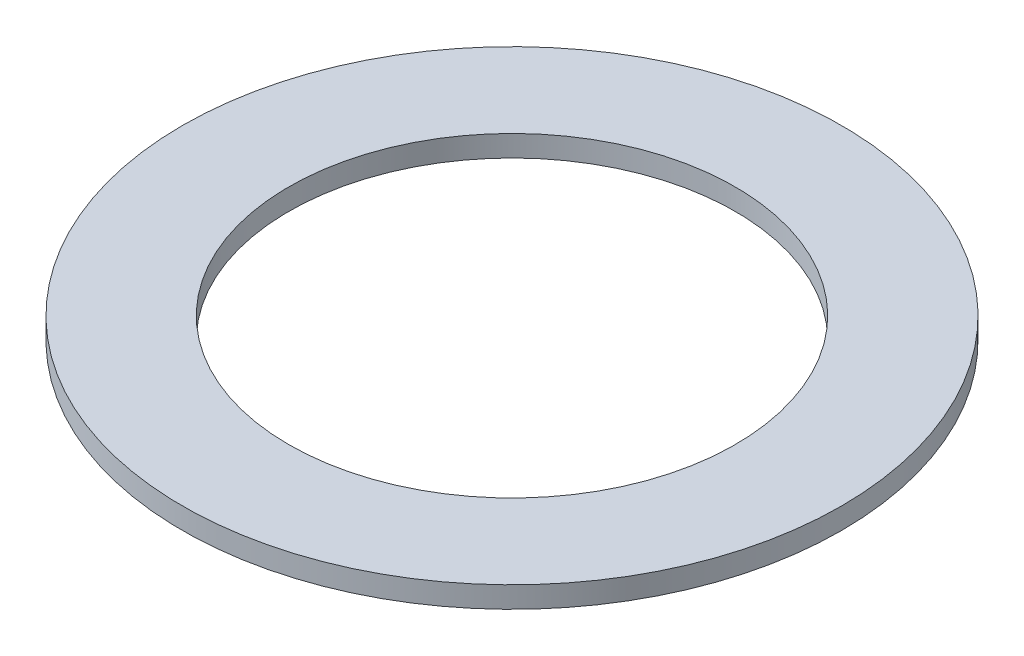
SolidWorks part; units mm, degrees
material "Plain Carbon Steel"
ref_plane "Front Plane" through (0, 0, 0) normal (0, 0, 1) x (1, 0, 0)
ref_plane "Top Plane" through (0, 0, 0) normal (0, 1, 0) x (1, 0, 0)
ref_plane "Right Plane" through (0, 0, 0) normal (1, 0, 0) x (0, 0, -1)
sketch "Sketch1" plane through (0, 0, 0) normal (0, 1, 0) x (1, 0, 0)
  circle A0 centre (0, 0) radius 10.5
  dimension "D1" = 21
extrude "Extrude-Thin1" add sketch "Sketch1" along normal blind 1 thin
